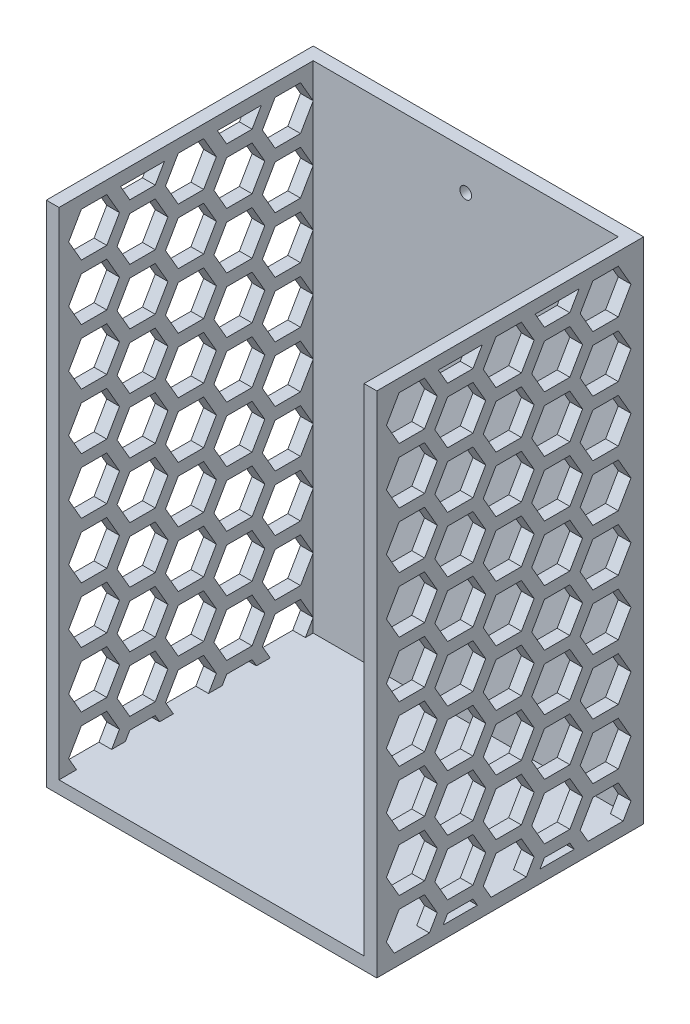
SolidWorks part; units mm, degrees
ref_plane "Front Plane" through (0, 0, 0) normal (0, 0, 1) x (1, 0, 0)
ref_plane "Top Plane" through (0, 0, 0) normal (0, 1, 0) x (1, 0, 0)
ref_plane "Right Plane" through (0, 0, 0) normal (1, 0, 0) x (0, 0, -1)
sketch "Sketch1" plane through (0, 0, 0) normal (0, 0, 1) x (1, 0, 0)
  line L1 (-65, -100) -> (65, -100)
  line L2 (-65, -100) -> (-65, 100)
  line L3 (-65, 100) -> (65, 100)
  line L4 (65, -100) -> (65, 100)
  line L5 (-65, -100) -> (65, 100) construction
  line L6 (-65, 100) -> (65, -100) construction
  point P0 (0, 0)
  dimension "D1" = 130
  dimension "D2" = 200
extrude "Boss-Extrude1" add sketch "Sketch1" along normal blind 5
sketch "Sketch2" plane through (0, 0, 0) normal (0, 0, 1) x (1, 0, 0)
  line L0 (65, 100) -> (-65, 100) construction
  line L1 (-65, -100) -> (65, -100) construction
  circle A0 centre (0, 85) radius 2.3
  circle A1 centre (0, -85) radius 2.3
  dimension "D1" = 4.6
  dimension "D2" = 15
  dimension "D3" = 15
extrude "Cut-Extrude2" cut sketch "Sketch2" along normal through all
sketch "Sketch3" plane through (0, 0, 5) normal (0, 0, 1) x (1, 0, 0)
  line L0 (-65, 100) -> (-65, -100) construction
  line L1 (-65, -95) -> (65, -95)
  line L2 (-65, -95) -> (-65, -100)
  line L3 (-65, -100) -> (65, -100)
  line L4 (65, -95) -> (65, -100)
  dimension "D1" = 5
extrude "Boss-Extrude2" add sketch "Sketch3" along normal blind 100
sketch "Sketch4" plane through (0, 0, 5) normal (0, 0, 1) x (1, 0, 0)
  line L0 (65, -95) -> (-65, -95) construction
  line L1 (-65, 100) -> (-60, 100)
  line L2 (-65, 100) -> (-65, -95)
  line L3 (-65, -95) -> (-60, -95)
  line L4 (-60, 100) -> (-60, -95)
  line L5 (65, -95) -> (-65, -95) construction
  line L6 (65, 100) -> (60, 100)
  line L7 (65, 100) -> (65, -95)
  line L8 (65, -95) -> (60, -95)
  line L9 (60, 100) -> (60, -95)
  dimension "D1" = 5
  dimension "D2" = 5
extrude "Boss-Extrude3" add sketch "Sketch4" along normal up to surface (100 mm away) up to face at (0, -97.5, 105)
sketch "Sketch5" plane through (-65, 0, 0) normal (-1, 0, 0) x (0, 0, 1)
  line L0 (20, -125) -> (10, -125)
  line L1 (20, 95) -> (10, 95)
  line L2 (10, 95) -> (5, 86.3397)
  line L3 (5, 86.3397) -> (10, 77.6795)
  line L4 (10, 77.6795) -> (20, 77.6795)
  line L5 (20, 77.6795) -> (25, 86.3397)
  line L6 (25, 86.3397) -> (20, 95)
  line L7 (0, 100) -> (0, -100) construction
  line L8 (39.0526, 106) -> (29.0526, 106)
  line L9 (29.0526, 106) -> (24.0526, 97.3397)
  line L10 (24.0526, 97.3397) -> (29.0526, 88.6795)
  line L11 (29.0526, 88.6795) -> (39.0526, 88.6795)
  line L12 (39.0526, 88.6795) -> (44.0526, 97.3397)
  line L13 (44.0526, 97.3397) -> (39.0526, 106)
  line L14 (58.1051, 117) -> (48.1051, 117)
  line L15 (48.1051, 117) -> (43.1051, 108.3397)
  line L16 (43.1051, 108.3397) -> (48.1051, 99.6795)
  line L17 (48.1051, 99.6795) -> (58.1051, 99.6795)
  line L18 (58.1051, 99.6795) -> (63.1051, 108.3397)
  line L19 (63.1051, 108.3397) -> (58.1051, 117)
  line L20 (77.1577, 128) -> (67.1577, 128)
  line L21 (67.1577, 128) -> (62.1577, 119.3397)
  line L22 (62.1577, 119.3397) -> (67.1577, 110.6795)
  line L23 (67.1577, 110.6795) -> (77.1577, 110.6795)
  line L24 (77.1577, 110.6795) -> (82.1577, 119.3397)
  line L25 (82.1577, 119.3397) -> (77.1577, 128)
  line L26 (96.2102, 139) -> (86.2102, 139)
  line L27 (86.2102, 139) -> (81.2102, 130.3397)
  line L28 (81.2102, 130.3397) -> (86.2102, 121.6795)
  line L29 (86.2102, 121.6795) -> (96.2102, 121.6795)
  line L30 (96.2102, 121.6795) -> (101.2102, 130.3397)
  line L31 (101.2102, 130.3397) -> (96.2102, 139)
  line L44 (39.0526, 84) -> (29.0526, 84)
  line L45 (29.0526, 84) -> (24.0526, 75.3397)
  line L46 (24.0526, 75.3397) -> (29.0526, 66.6795)
  line L47 (29.0526, 66.6795) -> (39.0526, 66.6795)
  line L48 (39.0526, 66.6795) -> (44.0526, 75.3397)
  line L49 (44.0526, 75.3397) -> (39.0526, 84)
  line L50 (58.1051, 95) -> (48.1051, 95)
  line L51 (48.1051, 95) -> (43.1051, 86.3397)
  line L52 (43.1051, 86.3397) -> (48.1051, 77.6795)
  line L53 (48.1051, 77.6795) -> (58.1051, 77.6795)
  line L54 (58.1051, 77.6795) -> (63.1051, 86.3397)
  line L55 (63.1051, 86.3397) -> (58.1051, 95)
  line L56 (77.1577, 106) -> (67.1577, 106)
  line L57 (67.1577, 106) -> (62.1577, 97.3397)
  line L58 (62.1577, 97.3397) -> (67.1577, 88.6795)
  line L59 (67.1577, 88.6795) -> (77.1577, 88.6795)
  line L60 (77.1577, 88.6795) -> (82.1577, 97.3397)
  line L61 (82.1577, 97.3397) -> (77.1577, 106)
  line L62 (96.2102, 117) -> (86.2102, 117)
  line L63 (86.2102, 117) -> (81.2102, 108.3397)
  line L64 (81.2102, 108.3397) -> (86.2102, 99.6795)
  line L65 (86.2102, 99.6795) -> (96.2102, 99.6795)
  line L66 (96.2102, 99.6795) -> (101.2102, 108.3397)
  line L67 (101.2102, 108.3397) -> (96.2102, 117)
  line L80 (39.0526, 62) -> (29.0526, 62)
  line L81 (29.0526, 62) -> (24.0526, 53.3397)
  line L82 (24.0526, 53.3397) -> (29.0526, 44.6795)
  line L83 (29.0526, 44.6795) -> (39.0526, 44.6795)
  line L84 (39.0526, 44.6795) -> (44.0526, 53.3397)
  line L85 (44.0526, 53.3397) -> (39.0526, 62)
  line L86 (58.1051, 73) -> (48.1051, 73)
  line L87 (48.1051, 73) -> (43.1051, 64.3397)
  line L88 (43.1051, 64.3397) -> (48.1051, 55.6795)
  line L89 (48.1051, 55.6795) -> (58.1051, 55.6795)
  line L90 (58.1051, 55.6795) -> (63.1051, 64.3397)
  line L91 (63.1051, 64.3397) -> (58.1051, 73)
  line L92 (77.1577, 84) -> (67.1577, 84)
  line L93 (67.1577, 84) -> (62.1577, 75.3397)
  line L94 (62.1577, 75.3397) -> (67.1577, 66.6795)
  line L95 (67.1577, 66.6795) -> (77.1577, 66.6795)
  line L96 (77.1577, 66.6795) -> (82.1577, 75.3397)
  line L97 (82.1577, 75.3397) -> (77.1577, 84)
  line L98 (96.2102, 95) -> (86.2102, 95)
  line L99 (86.2102, 95) -> (81.2102, 86.3397)
  line L100 (81.2102, 86.3397) -> (86.2102, 77.6795)
  line L101 (86.2102, 77.6795) -> (96.2102, 77.6795)
  line L102 (96.2102, 77.6795) -> (101.2102, 86.3397)
  line L103 (101.2102, 86.3397) -> (96.2102, 95)
  line L116 (39.0526, 40) -> (29.0526, 40)
  line L117 (29.0526, 40) -> (24.0526, 31.3397)
  line L118 (24.0526, 31.3397) -> (29.0526, 22.6795)
  line L119 (29.0526, 22.6795) -> (39.0526, 22.6795)
  line L120 (39.0526, 22.6795) -> (44.0526, 31.3397)
  line L121 (44.0526, 31.3397) -> (39.0526, 40)
  line L122 (58.1051, 51) -> (48.1051, 51)
  line L123 (48.1051, 51) -> (43.1051, 42.3397)
  line L124 (43.1051, 42.3397) -> (48.1051, 33.6795)
  line L125 (48.1051, 33.6795) -> (58.1051, 33.6795)
  line L126 (58.1051, 33.6795) -> (63.1051, 42.3397)
  line L127 (63.1051, 42.3397) -> (58.1051, 51)
  line L128 (77.1577, 62) -> (67.1577, 62)
  line L129 (67.1577, 62) -> (62.1577, 53.3397)
  line L130 (62.1577, 53.3397) -> (67.1577, 44.6795)
  line L131 (67.1577, 44.6795) -> (77.1577, 44.6795)
  line L132 (77.1577, 44.6795) -> (82.1577, 53.3397)
  line L133 (82.1577, 53.3397) -> (77.1577, 62)
  line L134 (96.2102, 73) -> (86.2102, 73)
  line L135 (86.2102, 73) -> (81.2102, 64.3397)
  line L136 (81.2102, 64.3397) -> (86.2102, 55.6795)
  line L137 (86.2102, 55.6795) -> (96.2102, 55.6795)
  line L138 (96.2102, 55.6795) -> (101.2102, 64.3397)
  line L139 (101.2102, 64.3397) -> (96.2102, 73)
  line L152 (39.0526, 18) -> (29.0526, 18)
  line L153 (29.0526, 18) -> (24.0526, 9.3397)
  line L154 (24.0526, 9.3397) -> (29.0526, 0.6795)
  line L155 (29.0526, 0.6795) -> (39.0526, 0.6795)
  line L156 (39.0526, 0.6795) -> (44.0526, 9.3397)
  line L157 (44.0526, 9.3397) -> (39.0526, 18)
  line L158 (58.1051, 29) -> (48.1051, 29)
  line L159 (48.1051, 29) -> (43.1051, 20.3397)
  line L160 (43.1051, 20.3397) -> (48.1051, 11.6795)
  line L161 (48.1051, 11.6795) -> (58.1051, 11.6795)
  line L162 (58.1051, 11.6795) -> (63.1051, 20.3397)
  line L163 (63.1051, 20.3397) -> (58.1051, 29)
  line L164 (77.1577, 40) -> (67.1577, 40)
  line L165 (67.1577, 40) -> (62.1577, 31.3397)
  line L166 (62.1577, 31.3397) -> (67.1577, 22.6795)
  line L167 (67.1577, 22.6795) -> (77.1577, 22.6795)
  line L168 (77.1577, 22.6795) -> (82.1577, 31.3397)
  line L169 (82.1577, 31.3397) -> (77.1577, 40)
  line L170 (96.2102, 51) -> (86.2102, 51)
  line L171 (86.2102, 51) -> (81.2102, 42.3397)
  line L172 (81.2102, 42.3397) -> (86.2102, 33.6795)
  line L173 (86.2102, 33.6795) -> (96.2102, 33.6795)
  line L174 (96.2102, 33.6795) -> (101.2102, 42.3397)
  line L175 (101.2102, 42.3397) -> (96.2102, 51)
  line L188 (39.0526, -4) -> (29.0526, -4)
  line L189 (29.0526, -4) -> (24.0526, -12.6603)
  line L190 (24.0526, -12.6603) -> (29.0526, -21.3205)
  line L191 (29.0526, -21.3205) -> (39.0526, -21.3205)
  line L192 (39.0526, -21.3205) -> (44.0526, -12.6603)
  line L193 (44.0526, -12.6603) -> (39.0526, -4)
  line L194 (58.1051, 7) -> (48.1051, 7)
  line L195 (48.1051, 7) -> (43.1051, -1.6603)
  line L196 (43.1051, -1.6603) -> (48.1051, -10.3205)
  line L197 (48.1051, -10.3205) -> (58.1051, -10.3205)
  line L198 (58.1051, -10.3205) -> (63.1051, -1.6603)
  line L199 (63.1051, -1.6603) -> (58.1051, 7)
  line L200 (77.1577, 18) -> (67.1577, 18)
  line L201 (67.1577, 18) -> (62.1577, 9.3397)
  line L202 (62.1577, 9.3397) -> (67.1577, 0.6795)
  line L203 (67.1577, 0.6795) -> (77.1577, 0.6795)
  line L204 (77.1577, 0.6795) -> (82.1577, 9.3397)
  line L205 (82.1577, 9.3397) -> (77.1577, 18)
  line L206 (96.2102, 29) -> (86.2102, 29)
  line L207 (86.2102, 29) -> (81.2102, 20.3397)
  line L208 (81.2102, 20.3397) -> (86.2102, 11.6795)
  line L209 (86.2102, 11.6795) -> (96.2102, 11.6795)
  line L210 (96.2102, 11.6795) -> (101.2102, 20.3397)
  line L211 (101.2102, 20.3397) -> (96.2102, 29)
  line L224 (39.0526, -26) -> (29.0526, -26)
  line L225 (29.0526, -26) -> (24.0526, -34.6603)
  line L226 (24.0526, -34.6603) -> (29.0526, -43.3205)
  line L227 (29.0526, -43.3205) -> (39.0526, -43.3205)
  line L228 (39.0526, -43.3205) -> (44.0526, -34.6603)
  line L229 (44.0526, -34.6603) -> (39.0526, -26)
  line L230 (58.1051, -15) -> (48.1051, -15)
  line L231 (48.1051, -15) -> (43.1051, -23.6603)
  line L232 (43.1051, -23.6603) -> (48.1051, -32.3205)
  line L233 (48.1051, -32.3205) -> (58.1051, -32.3205)
  line L234 (58.1051, -32.3205) -> (63.1051, -23.6603)
  line L235 (63.1051, -23.6603) -> (58.1051, -15)
  line L236 (77.1577, -4) -> (67.1577, -4)
  line L237 (67.1577, -4) -> (62.1577, -12.6603)
  line L238 (62.1577, -12.6603) -> (67.1577, -21.3205)
  line L239 (67.1577, -21.3205) -> (77.1577, -21.3205)
  line L240 (77.1577, -21.3205) -> (82.1577, -12.6603)
  line L241 (82.1577, -12.6603) -> (77.1577, -4)
  line L242 (96.2102, 7) -> (86.2102, 7)
  line L243 (86.2102, 7) -> (81.2102, -1.6603)
  line L244 (81.2102, -1.6603) -> (86.2102, -10.3205)
  line L245 (86.2102, -10.3205) -> (96.2102, -10.3205)
  line L246 (96.2102, -10.3205) -> (101.2102, -1.6603)
  line L247 (101.2102, -1.6603) -> (96.2102, 7)
  line L260 (39.0526, -48) -> (29.0526, -48)
  line L261 (29.0526, -48) -> (24.0526, -56.6603)
  line L262 (24.0526, -56.6603) -> (29.0526, -65.3205)
  line L263 (29.0526, -65.3205) -> (39.0526, -65.3205)
  line L264 (39.0526, -65.3205) -> (44.0526, -56.6603)
  line L265 (44.0526, -56.6603) -> (39.0526, -48)
  line L266 (58.1051, -37) -> (48.1051, -37)
  line L267 (48.1051, -37) -> (43.1051, -45.6603)
  line L268 (43.1051, -45.6603) -> (48.1051, -54.3205)
  line L269 (48.1051, -54.3205) -> (58.1051, -54.3205)
  line L270 (58.1051, -54.3205) -> (63.1051, -45.6603)
  line L271 (63.1051, -45.6603) -> (58.1051, -37)
  line L272 (77.1577, -26) -> (67.1577, -26)
  line L273 (67.1577, -26) -> (62.1577, -34.6603)
  line L274 (62.1577, -34.6603) -> (67.1577, -43.3205)
  line L275 (67.1577, -43.3205) -> (77.1577, -43.3205)
  line L276 (77.1577, -43.3205) -> (82.1577, -34.6603)
  line L277 (82.1577, -34.6603) -> (77.1577, -26)
  line L278 (96.2102, -15) -> (86.2102, -15)
  line L279 (86.2102, -15) -> (81.2102, -23.6603)
  line L280 (81.2102, -23.6603) -> (86.2102, -32.3205)
  line L281 (86.2102, -32.3205) -> (96.2102, -32.3205)
  line L282 (96.2102, -32.3205) -> (101.2102, -23.6603)
  line L283 (101.2102, -23.6603) -> (96.2102, -15)
  line L296 (39.0526, -70) -> (29.0526, -70)
  line L297 (29.0526, -70) -> (24.0526, -78.6603)
  line L298 (24.0526, -78.6603) -> (29.0526, -87.3205)
  line L299 (29.0526, -87.3205) -> (39.0526, -87.3205)
  line L300 (39.0526, -87.3205) -> (44.0526, -78.6603)
  line L301 (44.0526, -78.6603) -> (39.0526, -70)
  line L302 (58.1051, -59) -> (48.1051, -59)
  line L303 (48.1051, -59) -> (43.1051, -67.6603)
  line L304 (43.1051, -67.6603) -> (48.1051, -76.3205)
  line L305 (48.1051, -76.3205) -> (58.1051, -76.3205)
  line L306 (58.1051, -76.3205) -> (63.1051, -67.6603)
  line L307 (63.1051, -67.6603) -> (58.1051, -59)
  line L308 (77.1577, -48) -> (67.1577, -48)
  line L309 (67.1577, -48) -> (62.1577, -56.6603)
  line L310 (62.1577, -56.6603) -> (67.1577, -65.3205)
  line L311 (67.1577, -65.3205) -> (77.1577, -65.3205)
  line L312 (77.1577, -65.3205) -> (82.1577, -56.6603)
  line L313 (82.1577, -56.6603) -> (77.1577, -48)
  line L314 (96.2102, -37) -> (86.2102, -37)
  line L315 (86.2102, -37) -> (81.2102, -45.6603)
  line L316 (81.2102, -45.6603) -> (86.2102, -54.3205)
  line L317 (86.2102, -54.3205) -> (96.2102, -54.3205)
  line L318 (96.2102, -54.3205) -> (101.2102, -45.6603)
  line L319 (101.2102, -45.6603) -> (96.2102, -37)
  line L332 (39.0526, -92) -> (29.0526, -92)
  line L333 (29.0526, -92) -> (24.0526, -100.6603)
  line L334 (24.0526, -100.6603) -> (29.0526, -109.3205)
  line L335 (29.0526, -109.3205) -> (39.0526, -109.3205)
  line L336 (39.0526, -109.3205) -> (44.0526, -100.6603)
  line L337 (44.0526, -100.6603) -> (39.0526, -92)
  line L338 (58.1051, -81) -> (48.1051, -81)
  line L339 (48.1051, -81) -> (43.1051, -89.6603)
  line L340 (43.1051, -89.6603) -> (48.1051, -98.3205)
  line L341 (48.1051, -98.3205) -> (58.1051, -98.3205)
  line L342 (58.1051, -98.3205) -> (63.1051, -89.6603)
  line L343 (63.1051, -89.6603) -> (58.1051, -81)
  line L344 (77.1577, -70) -> (67.1577, -70)
  line L345 (67.1577, -70) -> (62.1577, -78.6603)
  line L346 (62.1577, -78.6603) -> (67.1577, -87.3205)
  line L347 (67.1577, -87.3205) -> (77.1577, -87.3205)
  line L348 (77.1577, -87.3205) -> (82.1577, -78.6603)
  line L349 (82.1577, -78.6603) -> (77.1577, -70)
  line L350 (96.2102, -59) -> (86.2102, -59)
  line L351 (86.2102, -59) -> (81.2102, -67.6603)
  line L352 (81.2102, -67.6603) -> (86.2102, -76.3205)
  line L353 (86.2102, -76.3205) -> (96.2102, -76.3205)
  line L354 (96.2102, -76.3205) -> (101.2102, -67.6603)
  line L355 (101.2102, -67.6603) -> (96.2102, -59)
  line L512 (20, 73) -> (10, 73)
  line L513 (10, 73) -> (5, 64.3397)
  line L514 (5, 64.3397) -> (10, 55.6795)
  line L515 (10, 55.6795) -> (20, 55.6795)
  line L516 (20, 55.6795) -> (25, 64.3397)
  line L517 (25, 64.3397) -> (20, 73)
  line L518 (20, 51) -> (10, 51)
  line L519 (10, 51) -> (5, 42.3397)
  line L520 (5, 42.3397) -> (10, 33.6795)
  line L521 (10, 33.6795) -> (20, 33.6795)
  line L522 (20, 33.6795) -> (25, 42.3397)
  line L523 (25, 42.3397) -> (20, 51)
  line L524 (20, 29) -> (10, 29)
  line L525 (10, 29) -> (5, 20.3397)
  line L526 (5, 20.3397) -> (10, 11.6795)
  line L527 (10, 11.6795) -> (20, 11.6795)
  line L528 (20, 11.6795) -> (25, 20.3397)
  line L529 (25, 20.3397) -> (20, 29)
  line L530 (20, 7) -> (10, 7)
  line L531 (10, 7) -> (5, -1.6603)
  line L532 (5, -1.6603) -> (10, -10.3205)
  line L533 (10, -10.3205) -> (20, -10.3205)
  line L534 (20, -10.3205) -> (25, -1.6603)
  line L535 (25, -1.6603) -> (20, 7)
  line L536 (20, -15) -> (10, -15)
  line L537 (10, -15) -> (5, -23.6603)
  line L538 (5, -23.6603) -> (10, -32.3205)
  line L539 (10, -32.3205) -> (20, -32.3205)
  line L540 (20, -32.3205) -> (25, -23.6603)
  line L541 (25, -23.6603) -> (20, -15)
  line L542 (20, -37) -> (10, -37)
  line L543 (10, -37) -> (5, -45.6603)
  line L544 (5, -45.6603) -> (10, -54.3205)
  line L545 (10, -54.3205) -> (20, -54.3205)
  line L546 (20, -54.3205) -> (25, -45.6603)
  line L547 (25, -45.6603) -> (20, -37)
  line L548 (20, -59) -> (10, -59)
  line L549 (10, -59) -> (5, -67.6603)
  line L550 (5, -67.6603) -> (10, -76.3205)
  line L551 (10, -76.3205) -> (20, -76.3205)
  line L552 (20, -76.3205) -> (25, -67.6603)
  line L553 (25, -67.6603) -> (20, -59)
  line L554 (20, -81) -> (10, -81)
  line L555 (10, -81) -> (5, -89.6603)
  line L556 (5, -89.6603) -> (10, -98.3205)
  line L557 (10, -98.3205) -> (20, -98.3205)
  line L558 (20, -98.3205) -> (25, -89.6603)
  line L559 (25, -89.6603) -> (20, -81)
  line L560 (20, -103) -> (10, -103)
  line L561 (10, -103) -> (5, -111.6603)
  line L562 (5, -111.6603) -> (10, -120.3205)
  line L563 (10, -120.3205) -> (20, -120.3205)
  line L564 (20, -120.3205) -> (25, -111.6603)
  line L565 (25, -111.6603) -> (20, -103)
  line L590 (20, 95) -> (39.0526, 106) construction
  line L591 (105, 100) -> (0, 100) construction
  line L592 (10, -125) -> (5, -133.6603)
  line L593 (5, -133.6603) -> (10, -142.3205)
  line L594 (10, -142.3205) -> (20, -142.3205)
  line L595 (20, -142.3205) -> (25, -133.6603)
  line L596 (25, -133.6603) -> (20, -125)
  line L597 (39.0526, -114) -> (29.0526, -114)
  line L598 (29.0526, -114) -> (24.0526, -122.6603)
  line L599 (24.0526, -122.6603) -> (29.0526, -131.3205)
  line L600 (29.0526, -131.3205) -> (39.0526, -131.3205)
  line L601 (39.0526, -131.3205) -> (44.0526, -122.6603)
  line L602 (44.0526, -122.6603) -> (39.0526, -114)
  line L603 (58.1051, -103) -> (48.1051, -103)
  line L604 (48.1051, -103) -> (43.1051, -111.6603)
  line L605 (43.1051, -111.6603) -> (48.1051, -120.3205)
  line L606 (48.1051, -120.3205) -> (58.1051, -120.3205)
  line L607 (58.1051, -120.3205) -> (63.1051, -111.6603)
  line L608 (63.1051, -111.6603) -> (58.1051, -103)
  line L609 (77.1577, -92) -> (67.1577, -92)
  line L610 (67.1577, -92) -> (62.1577, -100.6603)
  line L611 (62.1577, -100.6603) -> (67.1577, -109.3205)
  line L612 (67.1577, -109.3205) -> (77.1577, -109.3205)
  line L613 (77.1577, -109.3205) -> (82.1577, -100.6603)
  line L614 (82.1577, -100.6603) -> (77.1577, -92)
  line L615 (96.2102, -81) -> (86.2102, -81)
  line L616 (86.2102, -81) -> (81.2102, -89.6603)
  line L617 (81.2102, -89.6603) -> (86.2102, -98.3205)
  line L618 (86.2102, -98.3205) -> (96.2102, -98.3205)
  line L619 (96.2102, -98.3205) -> (101.2102, -89.6603)
  line L620 (101.2102, -89.6603) -> (96.2102, -81)
  circle A0 centre (15, 86.3397) radius 8.6603 construction
  dimension "D1" = 10
  dimension "D2" = 5
  dimension "D3" = 15
  dimension "D6" = 22
  dimension "D4" = 5
  dimension "D5" = 11
extrude "Cut-Extrude3" cut sketch "Sketch5" against normal through all
sketch "Sketch6" plane through (-65, 0, 0) normal (-1, 0, 0) x (0, 0, 1)
  line L0 (105, 100) -> (105, -100)
  line L1 (0, 100) -> (105, 100)
  line L2 (0, 100) -> (0, 95)
  line L3 (0, 95) -> (102, 95)
  line L5 (0, -100) -> (105, -100)
  line L6 (0, -100) -> (0, -95)
  line L7 (0, -95) -> (102, -95)
  line L12 (102, 95) -> (102, -95)
  line L13 (105, 100) -> (105, -100) construction
  dimension "D1" = 5
  dimension "D2" = 3
  dimension "D3" = 5
extrude "Boss-Extrude4" add sketch "Sketch6" against normal up to surface (5 mm away) up to face at (-60, 64.3397, 91.2102)
sketch "Sketch7" plane through (65, 0, 0) normal (1, 0, 0) x (0, 0, -1)
  line L1 (0, -100) -> (-105, -100)
  line L2 (0, -100) -> (0, -95)
  line L3 (0, -95) -> (-105, -95)
  line L4 (-105, -100) -> (-105, -95)
  dimension "D1" = 5
extrude "Boss-Extrude5" add sketch "Sketch7" against normal up to surface (130 mm away) up to face at (-65, -88.5534, 15)
sketch "Sketch8" plane through (65, 0, 0) normal (1, 0, 0) x (0, 0, -1)
  line L5 (-105, 100) -> (-105, -100)
  line L10 (0, 100) -> (-105, 100)
  line L11 (0, 100) -> (0, 95)
  line L12 (0, 95) -> (-102, 95)
  line L14 (-105, -100) -> (-105, 100) construction
  line L15 (-105, -100) -> (-102, -100)
  line L16 (-102, -100) -> (-102, 95)
  line L17 (-105, -100) -> (0, -100) construction
  dimension "D1" = 3
extrude "Boss-Extrude6" add sketch "Sketch8" against normal up to surface (5 mm away) up to face at (60, 64.3397, 91.2102)
